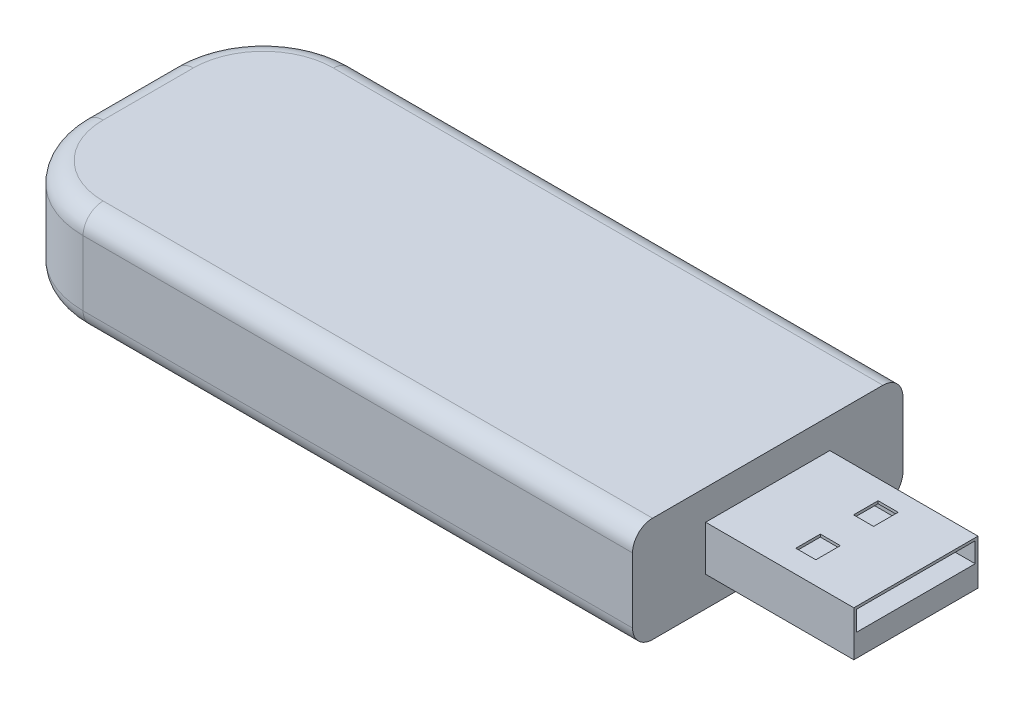
SolidWorks part; units mm, degrees
ref_plane "Front Plane" through (0, 0, 0) normal (0, 0, 1) x (1, 0, 0)
ref_plane "Top Plane" through (0, 0, 0) normal (0, 1, 0) x (1, 0, 0)
ref_plane "Right Plane" through (0, 0, 0) normal (1, 0, 0) x (0, 0, -1)
sketch "Sketch1" plane through (0, 0, 0) normal (0, 1, 0) x (1, 0, 0)
  line L0 (-22.6633, -19.2096) -> (-22.6633, 7.7904)
  line L1 (-77.5328, 7.7904) -> (-22.6633, 7.7904)
  line L2 (-86.5328, -1.2096) -> (-86.5328, -10.2096)
  line L3 (-77.5328, -19.2096) -> (-22.6633, -19.2096)
  line L5 (-22.6633, -15.2096) -> (-18.9545, -15.2096)
  arc A2 (-77.5328, 7.7904) -> (-86.5328, -1.2096) centre (-77.5328, -1.2096) ccw
  arc A3 (-77.5328, -19.2096) -> (-86.5328, -10.2096) centre (-77.5328, -10.2096) cw
  point P8 (-2.0328, -19.2096)
  point P11 (-86.5328, 7.7904)
  point P14 (-86.5328, -19.2096)
  dimension "D1" = 84.5
  dimension "D2" = 27
  dimension "D4" = 4
extrude "Boss-Extrude1" add sketch "Sketch1" along normal blind 10.5 contours A3 L3 L0 L1 A2 L2
fillet "Fillet3" radius 2 10 edges at (-86.5328, 10.5, 5.7096) (-83.8967, 10.5, -5.1544) (-50.098, 10.5, -7.7904) (-50.098, 10.5, 19.2096) (-83.8967, 10.5, 16.5735) (-86.5328, 0, 5.7096) (-83.8967, 0, -5.1544) (-50.098, 0, -7.7904) (-50.098, 0, 19.2096) (-83.8967, 0, 16.5735)
sketch "Sketch3" plane through (-22.6633, 0, 0) normal (1, 0, 0) x (0, 0, -1)
  line L0 (-19.2096, 8.5) -> (-19.2096, 2) construction
  line L1 (-11.9096, 7.5) -> (0.4904, 7.5)
  line L2 (-11.9096, 7.5) -> (-11.9096, 3)
  line L3 (-11.9096, 3) -> (0.4904, 3)
  line L4 (0.4904, 7.5) -> (0.4904, 3)
  line L6 (-17.2096, 10.5) -> (5.7904, 10.5) construction
  line L8 (-11.6443, 7.2386) -> (0.2103, 7.2386)
  line L9 (-11.6443, 7.2386) -> (-11.6443, 5.25)
  line L10 (-11.6443, 5.25) -> (0.2103, 5.25)
  line L11 (0.2103, 7.2386) -> (0.2103, 5.25)
  dimension "D1" = 12.4
  dimension "D2" = 4.5
  dimension "D3" = 7.3
  dimension "D4" = 3
extrude "Boss-Extrude2" add sketch "Sketch3" along normal blind 14.8
sketch "Sketch4" plane through (0, 7.5, 0) normal (0, 1, 0) x (1, 0, 0)
  line L1 (-15.9134, -1.4351) -> (-13.9134, -1.4351)
  line L2 (-15.9134, -1.4351) -> (-15.9134, -3.8851)
  line L3 (-15.9134, -3.8851) -> (-13.9134, -3.8851)
  line L4 (-13.9134, -1.4351) -> (-13.9134, -3.8851)
  line L5 (-15.9134, -7.205) -> (-13.9134, -7.205)
  line L6 (-15.9134, -7.205) -> (-15.9134, -9.655)
  line L7 (-15.9134, -9.655) -> (-13.9134, -9.655)
  line L8 (-13.9134, -7.205) -> (-13.9134, -9.655)
  dimension "D1" = 2
  dimension "D2" = 2.45
  dimension "D3" = 2
  dimension "D4" = 2.45
extrude "Cut-Extrude1" cut sketch "Sketch4" against normal blind 1
